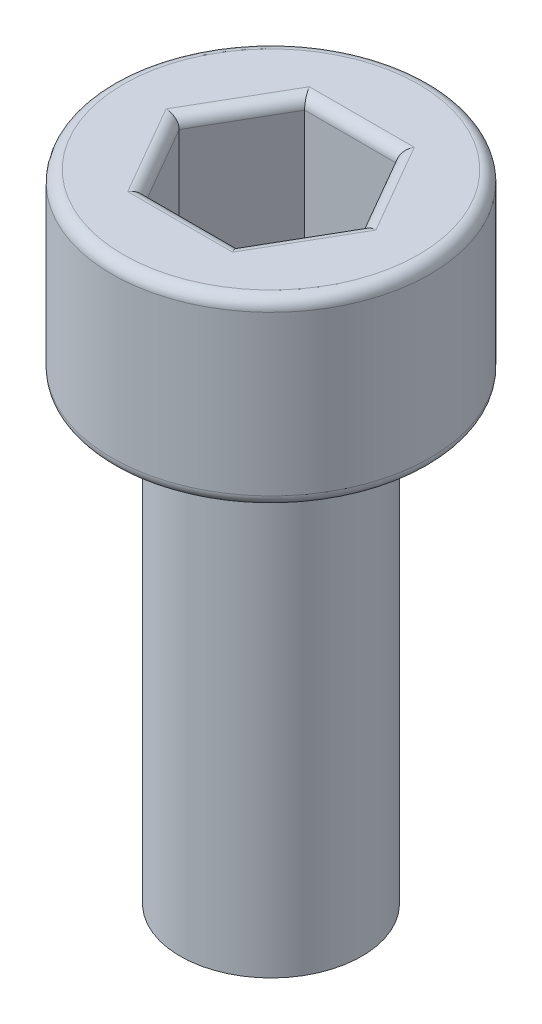
SolidWorks part; units mm, degrees
ref_plane "Front Plane" through (0, 0, 0) normal (0, 0, 1) x (1, 0, 0)
ref_plane "Top Plane" through (0, 0, 0) normal (0, 1, 0) x (1, 0, 0)
ref_plane "Right Plane" through (0, 0, 0) normal (1, 0, 0) x (0, 0, -1)
sketch "Sketch1" plane through (0, 0, 0) normal (0, 0, 1) x (1, 0, 0)
  line L0 (0, 21.3223) -> (0, -43.638) construction
sketch "Sketch2" plane through (0, 0, 0) normal (0, 0, 1) x (1, 0, 0)
  line L0 (0, 4) -> (3.5, 4)
  line L1 (0, 200021.3223) -> (0, -200043.638) construction
  line L2 (3.5, 4) -> (3.5, 0)
  line L3 (3.5, 0) -> (2, 0)
  line L4 (2, 0) -> (2, -10)
  line L5 (2, -10) -> (0, -10)
  line L6 (0, -10) -> (0, 4)
  dimension "D1" = 2
  dimension "D2" = 3.5
  dimension "D3" = 4
  dimension "D4" = 10
revolve "Revolve1" add sketch "Sketch2" angle 360 about L0
sketch "Sketch3" plane through (0, 4, 0) normal (0, 1, 0) x (1, 0, 0)
  line L0 (0, 0) -> (2.0207, 0) construction
  line L1 (2.0207, 0) -> (1.0104, 1.75)
  line L2 (1.0104, 1.75) -> (-1.0104, 1.75)
  line L3 (-1.0104, 1.75) -> (-2.0207, 0)
  line L4 (-2.0207, 0) -> (-1.0104, -1.75)
  line L5 (-1.0104, -1.75) -> (1.0104, -1.75)
  line L6 (1.0104, -1.75) -> (2.0207, 0)
  circle A0 centre (0, 0) radius 1.75 construction
  dimension "D1" = 3.5
extrude "Cut-Extrude1" cut sketch "Sketch3" against normal blind 3
fillet "Fillet1" radius 0.25 9 edges at (-2, 0, 0) (-3.5, 0, 0) (-3.5, 4, 0) (0, 4, -1.75) (-1.5155, 4, -0.875) (-1.5155, 4, 0.875) (0, 4, 1.75) (1.5155, 4, 0.875) (1.5155, 4, -0.875)
